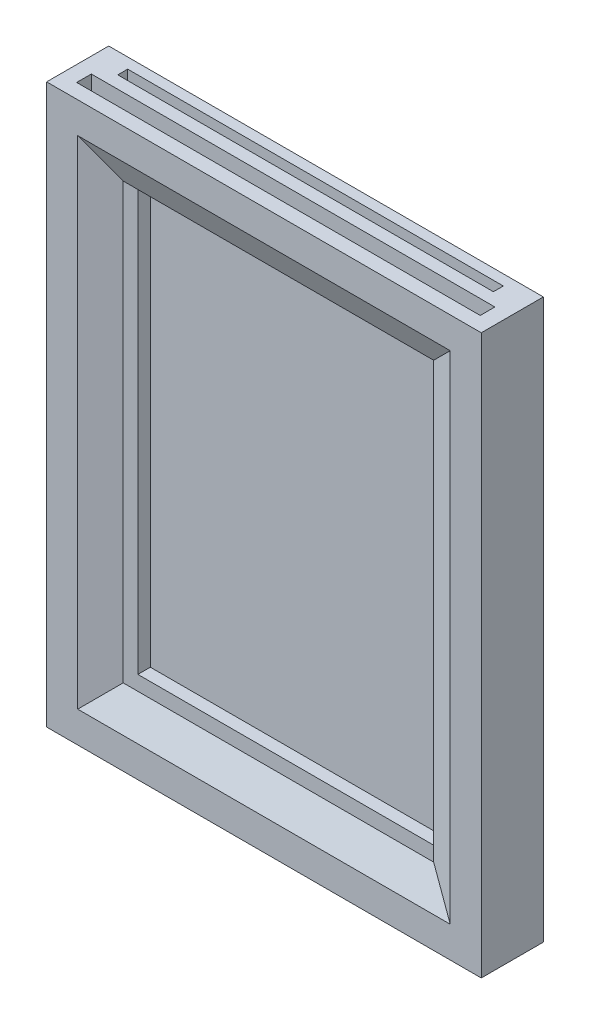
SolidWorks part; units mm, degrees
ref_plane "Front Plane" through (0, 0, 0) normal (0, 0, 1) x (1, 0, 0)
ref_plane "Top Plane" through (0, 0, 0) normal (0, 1, 0) x (1, 0, 0)
ref_plane "Right Plane" through (0, 0, 0) normal (1, 0, 0) x (0, 0, -1)
sketch "Sketch1" plane through (0, 0, 0) normal (0, 0, 1) x (1, 0, 0)
  line L1 (0, 0) -> (88.9, 0)
  line L2 (0, 0) -> (0, 114.3)
  line L3 (0, 114.3) -> (88.9, 114.3)
  line L4 (88.9, 0) -> (88.9, 114.3)
  dimension "D1" = 88.9
  dimension "D2" = 114.3
extrude "Boss-Extrude1" add sketch "Sketch1" along normal blind 12.7
sketch "Sketch2" plane through (0, 114.3, 0) normal (0, 1, 0) x (1, 0, 0)
  line L0 (0, -3.175) -> (88.9, -3.175) construction
  line L1 (6.0325, -4.191) -> (82.8675, -4.191)
  line L2 (6.0325, -4.191) -> (6.0325, -2.159)
  line L3 (6.0325, -2.159) -> (82.8675, -2.159)
  line L4 (82.8675, -4.191) -> (82.8675, -2.159)
  line L7 (44.45, 0) -> (44.45, -12.7) construction
  line L8 (88.9, 0) -> (0, 0) construction
  line L9 (88.9, -12.7) -> (0, -12.7) construction
  point P16 (44.45, -2.159)
  point P17 (82.8675, -3.175)
  dimension "D1" = 76.835
  dimension "D2" = 2.032
  dimension "D3" = 3.175
extrude "toploader_cut" cut sketch "Sketch2" against normal blind 105.41
sketch "Sketch3" plane through (0, 0, 12.7) normal (0, 0, 1) x (1, 0, 0)
  line L0 (44.45, 114.3) -> (44.45, 0) construction
  line L1 (12.7, 12.7) -> (76.2, 12.7)
  line L2 (12.7, 12.7) -> (12.7, 101.6)
  line L3 (12.7, 101.6) -> (76.2, 101.6)
  line L4 (76.2, 12.7) -> (76.2, 101.6)
  line L5 (88.9, 114.3) -> (0, 114.3) construction
  line L6 (0, 0) -> (88.9, 0) construction
  line L7 (0, 57.15) -> (88.9, 57.15) construction
  line L8 (0, 114.3) -> (0, 0) construction
  line L9 (88.9, 0) -> (88.9, 114.3) construction
  point P16 (44.45, 101.6)
  point P17 (12.7, 57.15)
  dimension "D1" = 63.5
  dimension "D2" = 88.9
extrude "viewing_window" cut sketch "Sketch3" against normal blind 9.525
chamfer "Chamfer1" distance 6.35 angle 25 4 edges at (44.45, 12.7, 12.7) (76.2, 57.15, 12.7) (44.45, 101.6, 12.7) (12.7, 57.15, 12.7)
sketch "acrylic_cut" plane through (0, 114.3, 0) normal (0, 1, 0) x (1, 0, 0)
  line L0 (0, -9.7389) -> (88.9, -9.7389) construction
  line L1 (3.175, -9.7389) -> (85.725, -9.7389)
  line L2 (3.175, -9.7389) -> (3.175, -6.7389)
  line L3 (3.175, -6.7389) -> (85.725, -6.7389)
  line L4 (85.725, -9.7389) -> (85.725, -6.7389)
  line L7 (44.45, 0) -> (44.45, -12.7) construction
  line L8 (88.9, 0) -> (0, 0) construction
  line L9 (88.9, -12.7) -> (0, -12.7) construction
  line L10 (0, -12.7) -> (0, 0) construction
  line L11 (88.9, -12.7) -> (88.9, 0) construction
  point P7 (44.45, -9.7389)
  dimension "D1" = 3
  dimension "D2" = 82.55
extrude "Cut-Extrude1" cut sketch "acrylic_cut" against normal blind 109.22
